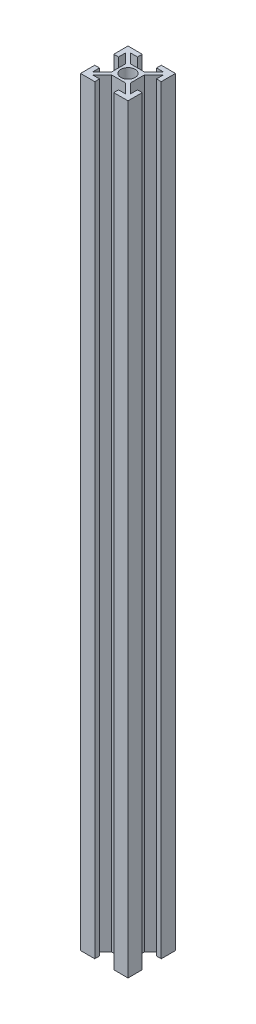
SolidWorks part; units mm, degrees
material "1060 Alloy"
ref_plane "Front Plane" through (0, 0, 0) normal (0, 0, 1) x (1, 0, 0)
ref_plane "Top Plane" through (0, 0, 0) normal (0, 1, 0) x (1, 0, 0)
ref_plane "Right Plane" through (0, 0, 0) normal (1, 0, 0) x (0, 0, -1)
sketch "2020 sketch" plane through (0, 0, 0) normal (0, 1, 0) x (1, 0, 0)
  line L0 (-4, 10) -> (-4, 8)
  line L1 (-10, 10) -> (-4, 10)
  line L2 (-10, 10) -> (-10, 4)
  line L3 (-10, -10) -> (-4, -10)
  line L4 (10, 10) -> (10, 4)
  line L5 (-10, 10) -> (10, -10) construction
  line L6 (-10, -10) -> (10, 10) construction
  line L7 (-4, 8) -> (-7, 8)
  line L8 (-7, 8) -> (-3, 4)
  line L9 (-3, 4) -> (3, 4)
  line L10 (3, 4) -> (7, 8)
  line L11 (7, 8) -> (4, 8)
  line L12 (4, 8) -> (4, 10)
  line L13 (4, 3) -> (4, -3)
  line L14 (8, 7) -> (4, 3)
  line L15 (8, 4) -> (8, 7)
  line L16 (10, 4) -> (8, 4)
  line L17 (8, -4) -> (10, -4)
  line L18 (8, -7) -> (8, -4)
  line L19 (4, -3) -> (8, -7)
  line L20 (3, -4) -> (-3, -4)
  line L21 (7, -8) -> (3, -4)
  line L22 (4, -8) -> (7, -8)
  line L23 (4, -10) -> (4, -8)
  line L24 (-4, -8) -> (-4, -10)
  line L25 (-7, -8) -> (-4, -8)
  line L26 (-3, -4) -> (-7, -8)
  line L27 (-4, -3) -> (-4, 3)
  line L28 (-8, -7) -> (-4, -3)
  line L29 (-8, -4) -> (-8, -7)
  line L30 (-10, -4) -> (-8, -4)
  line L31 (-8, 4) -> (-10, 4)
  line L32 (-8, 7) -> (-8, 4)
  line L33 (-4, 3) -> (-8, 7)
  line L34 (-10, -4) -> (-10, -10)
  line L35 (10, -4) -> (10, -10)
  line L36 (4, 10) -> (10, 10)
  line L37 (4, -10) -> (10, -10)
  circle A0 centre (0, 0) radius 3
  point P0 (0, 0)
  point P14 (4, 9)
  point P42 (0, 0)
  dimension "D9" = 6
  dimension "D1" = 20
  dimension "D2" = 20
  dimension "D3" = 8
  dimension "D4" = 6
  dimension "D5" = 6
  dimension "D6" = 2
  dimension "D7" = 4
  dimension "D8" = 4
extrude "Boss-Extrude1" add sketch "2020 sketch" along normal blind 320 contours A0 | L28 L27 L33 L32 L31 L2 L1 L0 L7 L8 L9 L10 L11 L12 L36 L4 L16 L15 L14 L13 L19 L18 L17 L35 L37 L23 L22 L21 L20 L26 L25 L24 L3 L34 L30 L29
